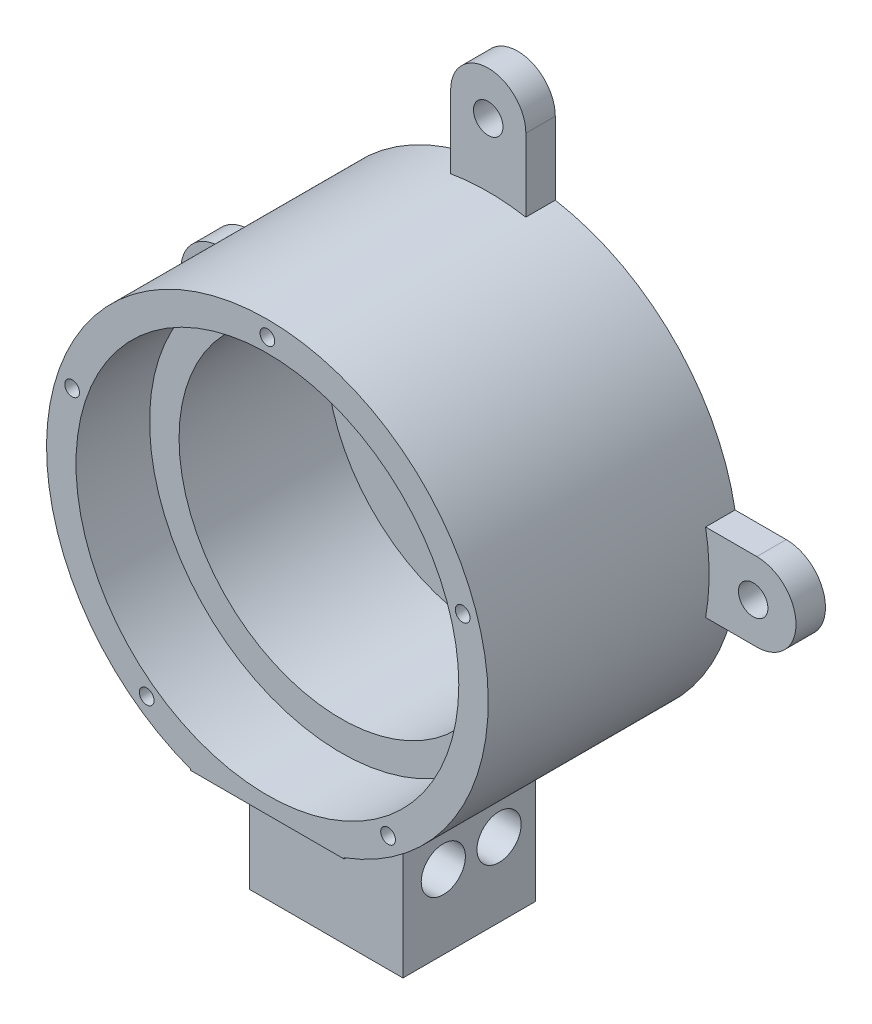
SolidWorks part; units mm, degrees
ref_plane "Front Plane" through (0, 0, 0) normal (1, 0, 0) x (0, 1, 0)
ref_plane "Top Plane" through (0, 0, 0) normal (0, 0, 1) x (0, 1, 0)
ref_plane "Right Plane" through (0, 0, 0) normal (0, 1, 0) x (-1, 0, 0)
sketch "Sketch2" plane through (0, 0, 0) normal (0, 0, 1) x (0, 1, 0)
  circle A0 centre (0, 0) radius 75
  dimension "D1" = 150
extrude "Boss-Extrude1" add sketch "Sketch2" along normal blind 85 contours A0
sketch "Sketch4" plane through (0, 0, 85) normal (0, 0, 1) x (1, 0, 0)
  circle A0 centre (0, 0) radius 65
  dimension "D1" = 130
extrude "Cut-Extrude2" cut sketch "Sketch4" against normal blind 25
sketch "Sketch5" plane through (0, 0, 60) normal (0, 0, 1) x (1, 0, 0)
  circle A0 centre (0, 0) radius 55
  dimension "D1" = 110
extrude "Cut-Extrude3" cut sketch "Sketch5" against normal blind 50
sketch "Sketch7" plane through (0, 0, 85) normal (0, 0, 1) x (1, 0, 0)
  circle A0 centre (0, 69.7234) radius 2.5
  dimension "D1" = 5
extrude "Cut-Extrude4" cut sketch "Sketch7" against normal blind 20
pattern_circular "CirPattern1" count 5 over 360 about axis through (0, 0, 0) along (0, 0, 1) of "Cut-Extrude4"
sketch "Sketch15" plane through (0, 0, 0) normal (0, 0, -1) x (1, 0, 0)
  line L0 (0, 70.335) -> (26.0382, 70.335)
  line L1 (26.0382, 70.335) -> (26.0382, 115.7075)
  line L2 (26.0382, 115.7075) -> (-26.0382, 115.7075)
  line L3 (-26.0382, 115.7075) -> (-26.0382, 70.335)
  line L4 (-26.0382, 70.335) -> (0, 70.335)
  circle A0 centre (0, 0) radius 75 construction
extrude "Boss-Extrude2" add sketch "Sketch15" against normal blind 85
sketch "Sketch29" plane through (0, -115.7075, 0) normal (0, -1, 0) x (1, 0, 0)
  line L0 (26.0382, 85) -> (26.0382, 0) construction
  line L1 (-26.0382, 85) -> (26.0382, 85)
  line L2 (-26.0382, 85) -> (-26.0382, 65)
  line L3 (-26.0382, 65) -> (26.0382, 65)
  line L4 (26.0382, 85) -> (26.0382, 65)
  line L5 (26.0382, 85) -> (26.0382, 0) construction
  line L6 (-26.0382, 0) -> (26.0382, 0)
  line L7 (-26.0382, 0) -> (-26.0382, 20)
  line L8 (-26.0382, 20) -> (26.0382, 20)
  line L9 (26.0382, 0) -> (26.0382, 20)
  dimension "D1" = 20
  dimension "D2" = 20
extrude "Cut-Extrude9" cut sketch "Sketch29" against normal blind 45 and the other way through all
sketch "Sketch23" plane through (-26.0382, 0, 0) normal (-1, 0, 0) x (0, -1, 0)
  circle A0 centre (90.5569, 51.2993) radius 7.5
  circle A1 centre (90.5569, 32.3617) radius 7.5
  dimension "D1" = 15
extrude "Cut-Extrude8" cut sketch "Sketch23" against normal through all
sketch "Sketch30" plane through (0, 0, 0) normal (0, 0, -1) x (1, 0, 0)
  line L0 (-91.0601, 0) -> (91.1976, 0) construction
  line L1 (-91.0601, 13.3132) -> (91.1976, 13.3132)
  line L2 (-91.0601, -13.3132) -> (91.1976, -13.3132)
  arc A0 (-91.0601, 13.3132) -> (-91.0601, -13.3132) centre (-91.0601, 0) ccw
  arc A1 (91.1976, -13.3132) -> (91.1976, 13.3132) centre (91.1976, 0) ccw
  point P3 (0.0687, 0)
extrude "Boss-Extrude4" add sketch "Sketch30" against normal blind 10
sketch "Sketch31" plane through (0, 0, 0) normal (0, 0, -1) x (1, 0, 0)
  line L0 (0, -41.534) -> (0, -98.5893) construction
  line L1 (12.7682, -41.534) -> (12.7682, -98.5893)
  line L2 (-12.7682, -41.534) -> (-12.7682, -98.5893)
  arc A0 (12.7682, -41.534) -> (-12.7682, -41.534) centre (0, -41.534) ccw
  arc A1 (-12.7682, -98.5893) -> (12.7682, -98.5893) centre (0, -98.5893) ccw
  point P3 (0, -70.0616)
extrude "Boss-Extrude5" add sketch "Sketch31" against normal blind 10
sketch "Sketch32" plane through (0, 0, 10) normal (0, 0, 1) x (1, 0, 0)
  circle A0 centre (-89.5338, 0) radius 5
  circle A1 centre (0, 96.5646) radius 5
  circle A2 centre (89.966, 0) radius 5
  dimension "D1" = 10
extrude "Cut-Extrude10" cut sketch "Sketch32" against normal blind 10
